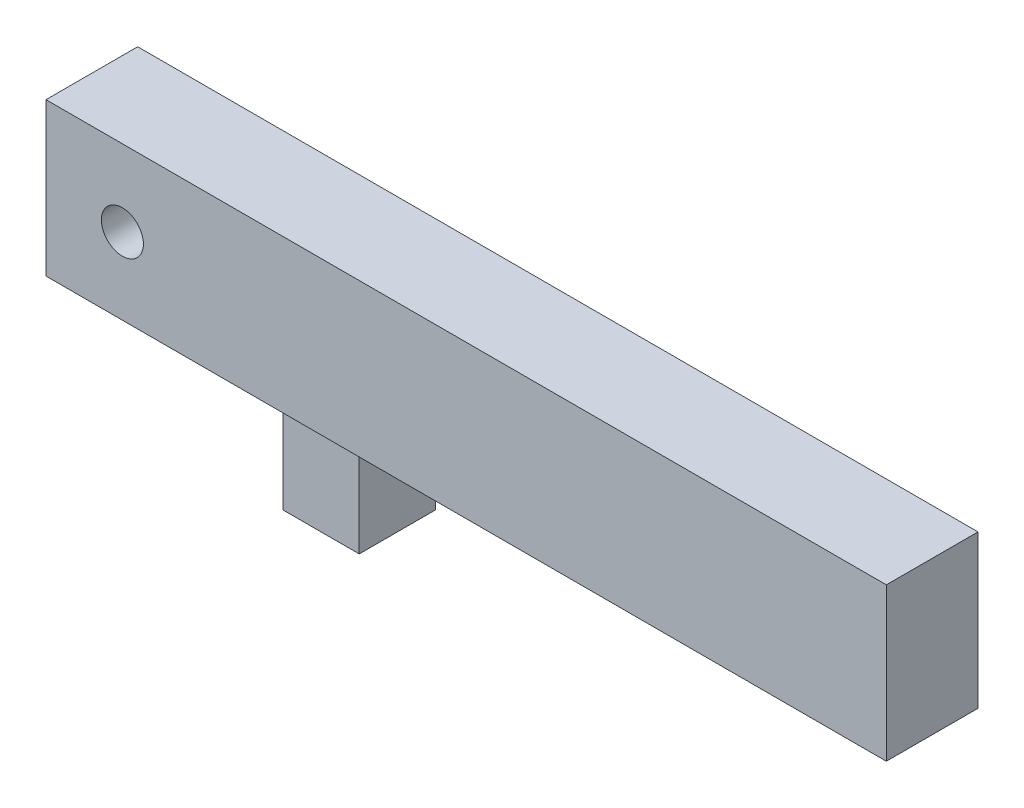
SolidWorks part; units mm, degrees
ref_plane "Front Plane" through (0, 0, 0) normal (0, 0, 1) x (1, 0, 0)
ref_plane "Top Plane" through (0, 0, 0) normal (0, 1, 0) x (1, 0, 0)
ref_plane "Right Plane" through (0, 0, 0) normal (1, 0, 0) x (0, 0, -1)
sketch "Sketch1" plane through (0, 0, 0) normal (0, 0, 1) x (1, 0, 0)
  line L1 (0, 0) -> (110, 0)
  line L2 (0, 0) -> (0, 20)
  line L3 (0, 20) -> (110, 20)
  line L4 (110, 0) -> (110, 20)
  dimension "D1" = 110
  dimension "D2" = 20
extrude "Boss-Extrude1" add sketch "Sketch1" along normal blind 12
sketch "Sketch2" plane through (0, 0, 12) normal (0, 0, 1) x (1, 0, 0)
  line L0 (110, 20) -> (0, 20) construction
  line L1 (0, 20) -> (0, 0) construction
  circle A0 centre (10, 10) radius 2.75
  dimension "D1" = 5.5
  dimension "D2" = 10
  dimension "D3" = 10
extrude "Cut-Extrude1" cut sketch "Sketch2" against normal through all both and the other way through all
sketch "Sketch3" plane through (0, 0, 0) normal (0, -1, 0) x (1, 0, 0)
  line L0 (0, 12) -> (0, 0) construction
  line L1 (30, 11) -> (40, 11)
  line L2 (30, 11) -> (30, 1)
  line L3 (30, 1) -> (40, 1)
  line L4 (40, 11) -> (40, 1)
  line L5 (0, 12) -> (110, 12) construction
  dimension "D1" = 10
  dimension "D2" = 10
  dimension "D3" = 30
  dimension "D4" = 1
extrude "Boss-Extrude2" add sketch "Sketch3" along normal blind 12
